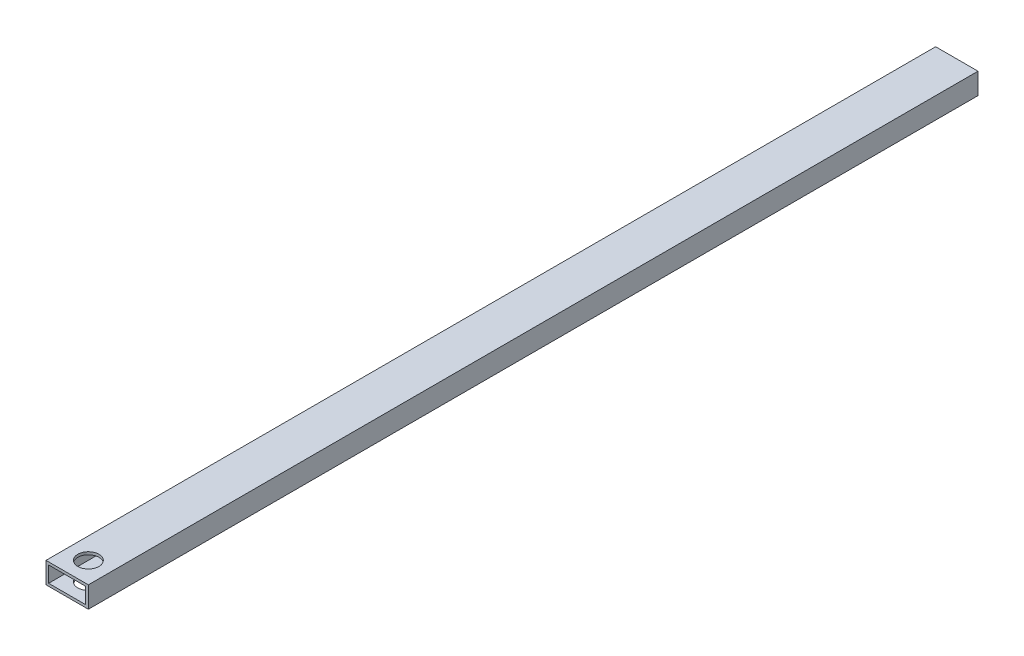
SolidWorks part; units mm, degrees
ref_plane "Front Plane" through (0, 0, 0) normal (0, 0, 1) x (1, 0, 0)
ref_plane "Top Plane" through (0, 0, 0) normal (0, 1, 0) x (1, 0, 0)
ref_plane "Right Plane" through (0, 0, 0) normal (1, 0, 0) x (0, 0, -1)
sketch "Sketch1" plane through (0, 0, 0) normal (0, 0, 1) x (1, 0, 0)
  line L1 (0, 0) -> (50.8, 0)
  line L2 (0, 0) -> (0, 25.4)
  line L3 (0, 25.4) -> (50.8, 25.4)
  line L4 (50.8, 0) -> (50.8, 25.4)
  dimension "D1" = 50.8
  dimension "D2" = 25.4
extrude "Boss-Extrude2" add sketch "Sketch1" along normal blind 1066.8
sketch "Sketch3" plane through (0, 0, 1066.8) normal (0, 0, 1) x (1, 0, 0)
  line L0 (0, 0) -> (50.8, 0) construction
  line L1 (50.8, 25.4) -> (0, 25.4) construction
  line L2 (3.175, 22.225) -> (47.625, 22.225)
  line L3 (3.175, 22.225) -> (3.175, 3.175)
  line L4 (3.175, 3.175) -> (47.625, 3.175)
  line L5 (47.625, 22.225) -> (47.625, 3.175)
  line L6 (50.8, 0) -> (50.8, 25.4) construction
  line L7 (0, 25.4) -> (0, 0) construction
  dimension "D1" = 3.175
  dimension "D2" = 3.175
  dimension "D3" = 3.175
  dimension "D4" = 3.175
extrude "Cut-Extrude2" cut sketch "Sketch3" against normal through all both
sketch "Sketch4" plane through (0, 25.4, 0) normal (0, 1, 0) x (1, 0, 0)
  line L0 (50.8, -1066.8) -> (0, -1066.8) construction
  line L1 (0, -1066.8) -> (0, 0) construction
  circle A0 centre (25.4, -1041.4) radius 12.7
  dimension "D3" = 25.4
  dimension "D1" = 25.4
  dimension "D2" = 25.4
extrude "Cut-Extrude3" cut sketch "Sketch4" against normal through all both and the other way through all
